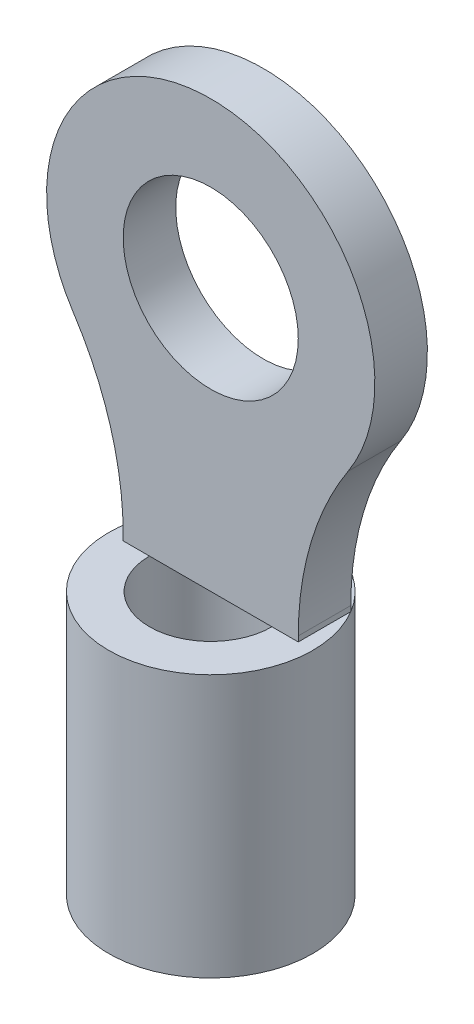
SolidWorks part; units mm, degrees
ref_plane "正面" through (0, 0, 0) normal (0, 0, 1) x (1, 0, 0)
ref_plane "平面" through (0, 0, 0) normal (0, 1, 0) x (1, 0, 0)
ref_plane "右側面" through (0, 0, 0) normal (1, 0, 0) x (0, 0, -1)
sketch "ｽｹｯﾁ1" plane through (0, 0, 0) normal (0, 0, 1) x (1, 0, 0)
  line L0 (0, 0) -> (0, -1.5) construction
  line L1 (-0.5, -1.5) -> (0.5, -1.5)
  line L2 (-0.5, -1.4697) -> (-0.5, -1.5)
  line L3 (0.5, -1.5) -> (0.5, -1.4697)
  arc A0 (0.7849, -0.5127) -> (-0.7849, -0.5127) centre (0, 0) ccw
  circle A1 centre (0, 0) radius 0.5
  arc A2 (0.5, -1.4697) -> (0.7849, -0.5127) centre (2.25, -1.4697) cw
  arc A3 (-0.5, -1.4697) -> (-0.7849, -0.5127) centre (-2.25, -1.4697) ccw
  dimension "D1" = 1.875
  dimension "D2" = 1
  dimension "D5" = 1.75
  dimension "D3" = 1.5
  dimension "D4" = 1
extrude "ﾎﾞｽ - 押し出し1" add sketch "ｽｹｯﾁ1" along normal blind 0.3
ref_plane "平面3" through (0, -3.5, 0) normal (0, -1, 0) x (-1, 0, 0)
sketch "ｽｹｯﾁ16" plane through (0, -1.5, 0) normal (0, -1, 0) x (-1, 0, 0)
  line L0 (0.5, -0.3) -> (-0.5, -0.3) construction
  circle A0 centre (0, -0.3) radius 0.5831
  circle A1 centre (0, -0.3) radius 0.35
  dimension "D1" = 0.7
extrude "ﾎﾞｽ - 押し出し5" add sketch "ｽｹｯﾁ16" along normal blind 1.5
